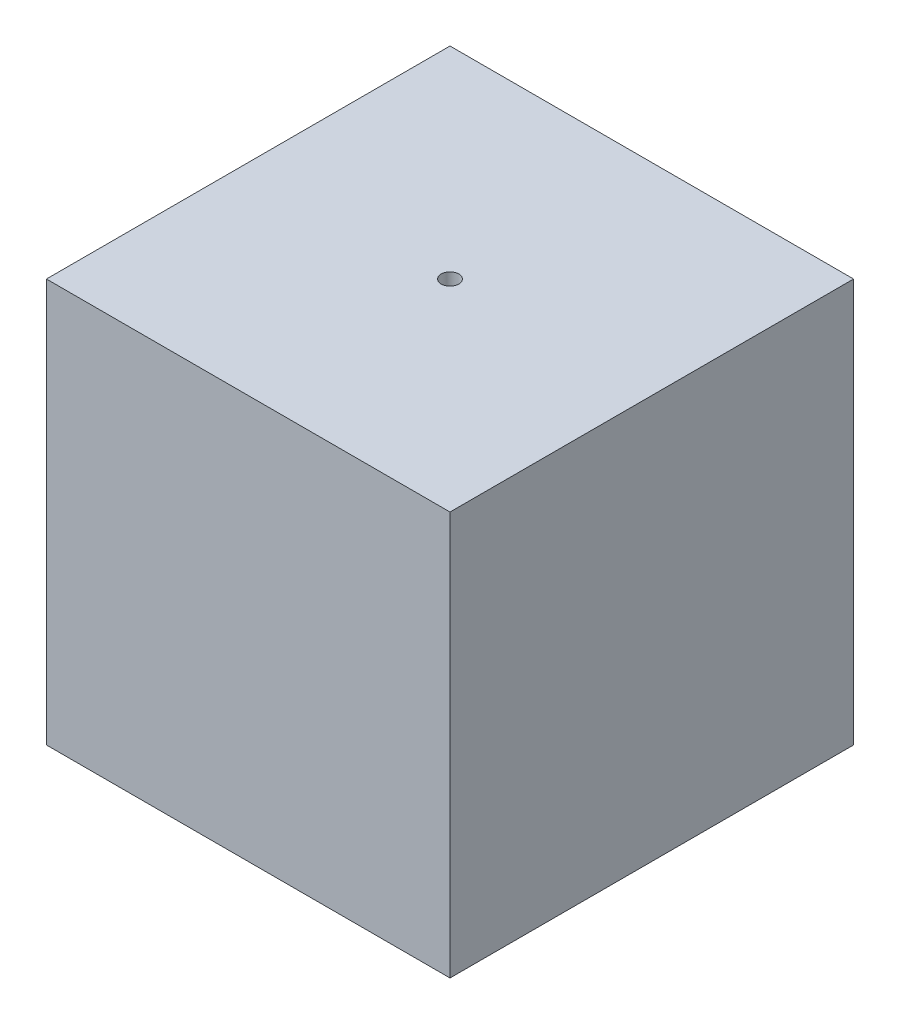
SolidWorks part; units mm, degrees
material "Hexcel AS4C (3000 filamentos)"
ref_plane "Alzado" through (0, 0, 0) normal (0, 0, 1) x (1, 0, 0)
ref_plane "Planta" through (0, 0, 0) normal (0, 1, 0) x (1, 0, 0)
ref_plane "Vista lateral" through (0, 0, 0) normal (1, 0, 0) x (0, 0, -1)
sketch "Croquis1" plane through (0, 0, 0) normal (0, 1, 0) x (1, 0, 0)
  line L1 (0, 0) -> (230, 0)
  line L2 (0, 0) -> (0, 230)
  line L3 (0, 230) -> (230, 230)
  line L4 (230, 0) -> (230, 230)
  dimension "D1" = 230
  dimension "D2" = 230
extrude "Saliente-Extruir1" add sketch "Croquis1" along normal blind 230
sketch "Croquis2" plane through (0, 230, 0) normal (0, 1, 0) x (1, 0, 0)
  line L0 (0, 230) -> (230, 0)
  line L1 (230, 0) -> (230, 230)
  line L2 (230, 230) -> (0, 0)
  circle A0 centre (115, 115) radius 5
extrude "Cortar-Extruir1" cut sketch "Croquis2" against normal blind 10 contours A0
